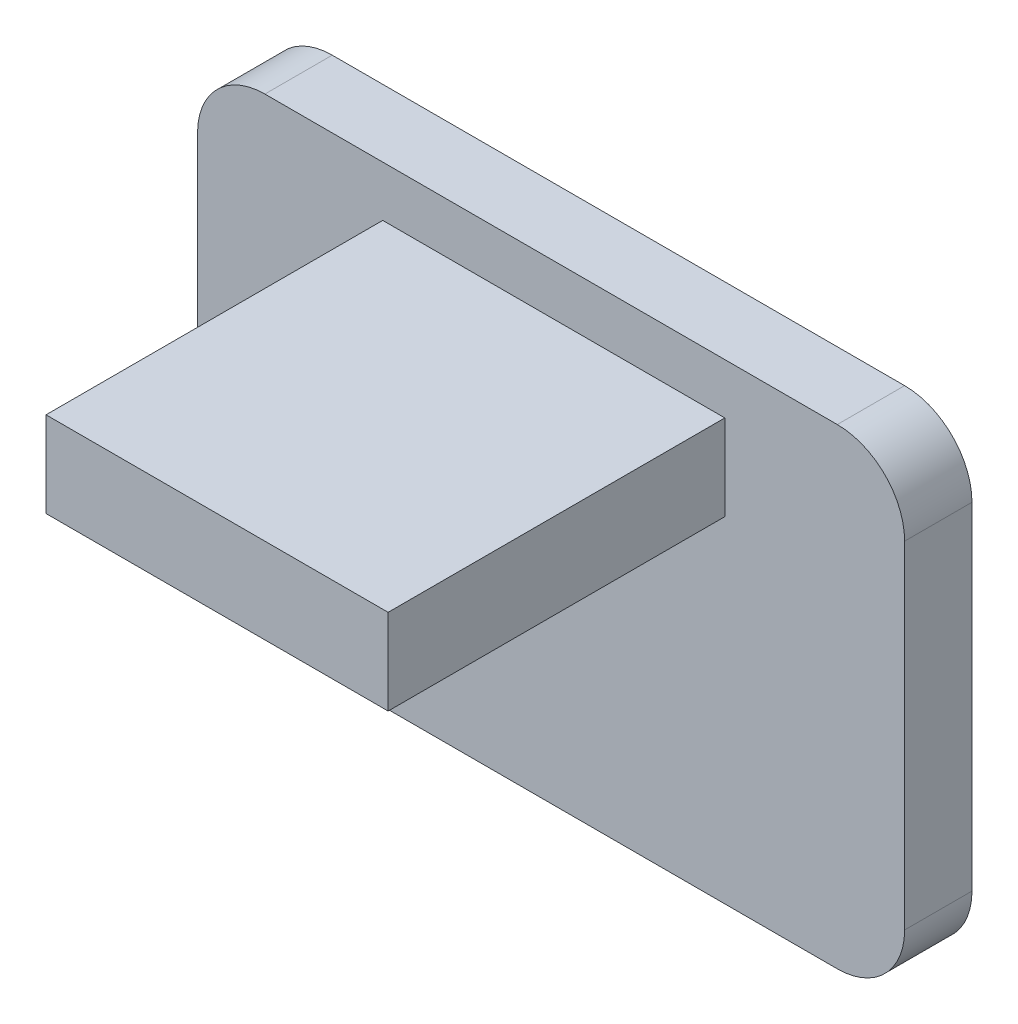
SolidWorks part; units mm, degrees
ref_plane "Płaszczyzna przednia" through (0, 0, 0) normal (0, 0, 1) x (1, 0, 0)
ref_plane "Płaszczyzna górna" through (0, 0, 0) normal (0, 1, 0) x (1, 0, 0)
ref_plane "Płaszczyzna prawa" through (0, 0, 0) normal (1, 0, 0) x (0, 0, -1)
sketch "Szkic1" plane through (0, 0, 0) normal (0, 0, 1) x (1, 0, 0)
  line L1 (-8.9323, 11.4941) -> (8.0677, 11.4941)
  line L2 (-10.9323, 9.4941) -> (-10.9323, -0.5059)
  line L3 (-8.9323, -2.5059) -> (8.0677, -2.5059)
  line L4 (10.0677, 9.4941) -> (10.0677, -0.5059)
  arc A0 (-8.9323, 11.4941) -> (-10.9323, 9.4941) centre (-8.9323, 9.4941) ccw
  arc A1 (-10.9323, -0.5059) -> (-8.9323, -2.5059) centre (-8.9323, -0.5059) ccw
  arc A2 (8.0677, -2.5059) -> (10.0677, -0.5059) centre (8.0677, -0.5059) ccw
  arc A3 (8.0677, 11.4941) -> (10.0677, 9.4941) centre (8.0677, 9.4941) cw
  point P6 (-10.9323, 11.4941)
  point P9 (-10.9323, -2.5059)
  point P14 (10.0677, 11.4941)
  dimension "D3" = 2
  dimension "D1" = 21
  dimension "D2" = 14
extrude "Dodanie-wyciągnięcie1" add sketch "Szkic1" along normal blind 2 contours L1 A3 L4 A2 L3 A1 L2 A0
sketch "Szkic2" plane through (0, 0, 2) normal (0, 0, 1) x (1, 0, 0)
  line L0 (-8.9323, 11.4941) -> (8.0677, 11.4941) construction
  line L1 (-5.4323, 9.9941) -> (4.7277, 9.9941)
  line L2 (-5.4323, 9.9941) -> (-5.4323, 7.4541)
  line L3 (-5.4323, 7.4541) -> (4.7277, 7.4541)
  line L4 (4.7277, 9.9941) -> (4.7277, 7.4541)
  line L5 (-10.9323, 9.4941) -> (-10.9323, -0.5059) construction
  dimension "D1" = 10.16
  dimension "D2" = 2.54
  dimension "D3" = 1.5
  dimension "D4" = 5.5
extrude "Dodanie-wyciągnięcie2" add sketch "Szkic2" along normal blind 10
